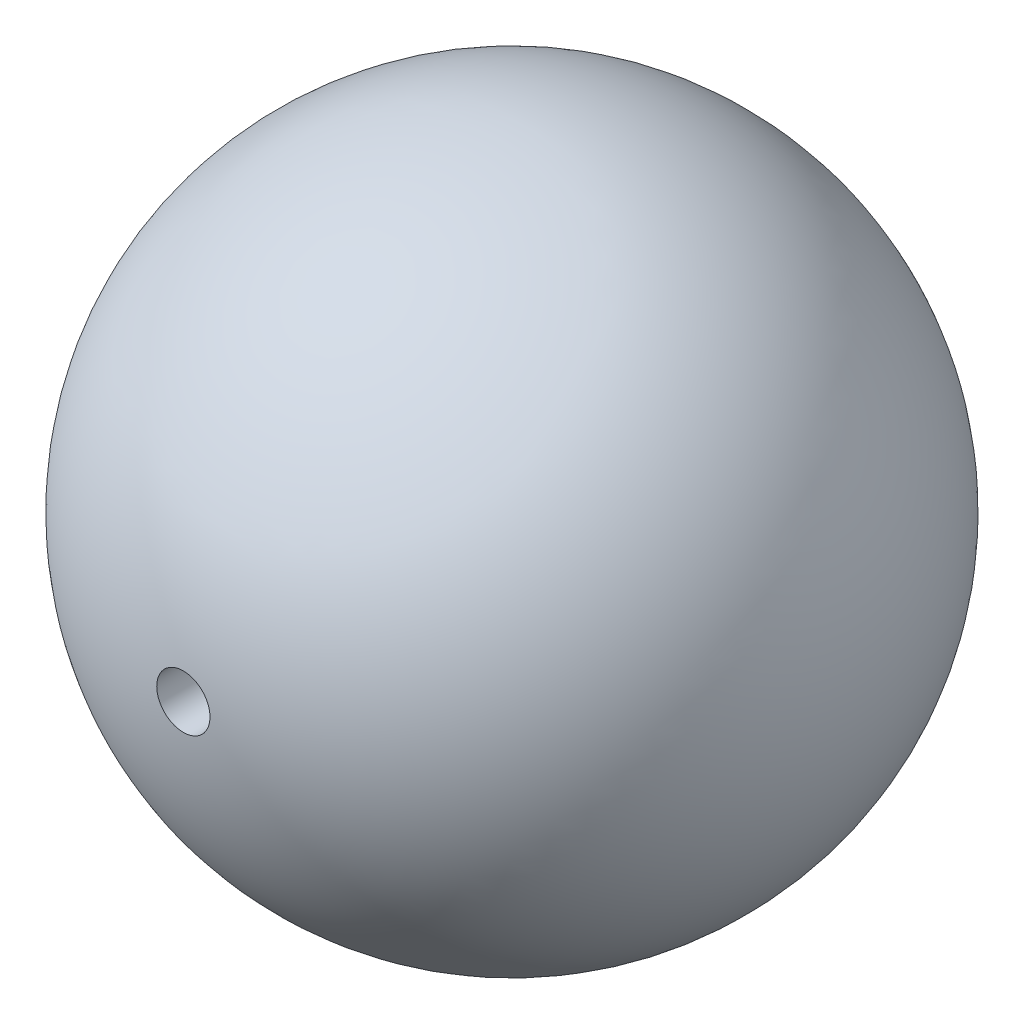
SolidWorks part; units mm, degrees
ref_plane "前视基准面" through (0, 0, 0) normal (0, 0, 1) x (1, 0, 0)
ref_plane "上视基准面" through (0, 0, 0) normal (0, 1, 0) x (1, 0, 0)
ref_plane "右视基准面" through (0, 0, 0) normal (1, 0, 0) x (0, 0, -1)
sketch "草图1" plane through (0, 0, 0) normal (0, 1, 0) x (1, 0, 0)
  line L0 (0, 0) -> (0, 9.9) construction
  line L1 (0, 9.9) -> (0, -9.9)
  arc A0 (0, 9.9) -> (0, -9.9) centre (0, 0) cw
  dimension "D1" = 9.9
revolve "旋转1" add sketch "草图1" angle 360 about L0
sketch "草图3" plane through (0, 0, 0) normal (0, 0, 1) x (1, 0, 0)
  circle A0 centre (0, 0) radius 0.8
  dimension "D1" = 1.6
extrude "切除-拉伸1" cut sketch "草图3" against normal through all and the other way through all
